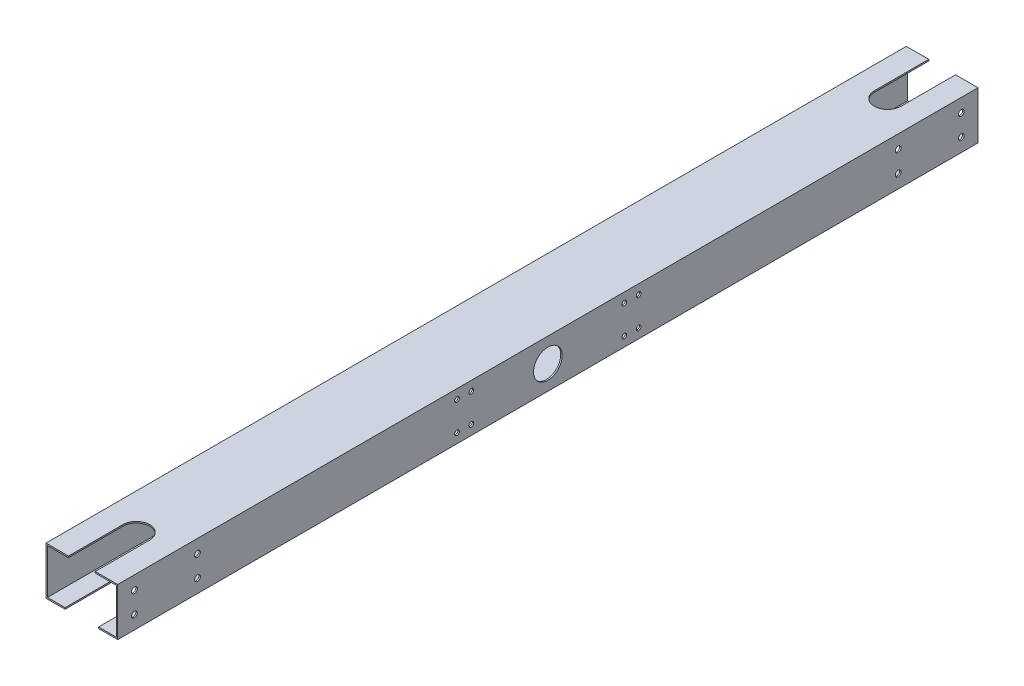
SolidWorks part; units mm, degrees
material "6061 Alloy"
ref_plane "Front Plane" through (0, 0, 0) normal (0, 0, 1) x (1, 0, 0)
ref_plane "Top Plane" through (0, 0, 0) normal (0, 1, 0) x (1, 0, 0)
ref_plane "Right Plane" through (0, 0, 0) normal (1, 0, 0) x (0, 0, -1)
sketch "Sketch1" plane through (0, 0, 0) normal (0, 0, 1) x (1, 0, 0)
  line L1 (-36, 23.5) -> (36, 23.5)
  line L2 (-36, 23.5) -> (-36, -23.5)
  line L3 (-36, -23.5) -> (36, -23.5)
  line L4 (36, 23.5) -> (36, -23.5)
  line L5 (-36, 23.5) -> (36, -23.5) construction
  line L6 (-36, -23.5) -> (36, 23.5) construction
  line L7 (-37.5, 25) -> (37.5, 25)
  line L8 (-37.5, 25) -> (-37.5, -25)
  line L9 (-37.5, -25) -> (37.5, -25)
  line L10 (37.5, 25) -> (37.5, -25)
  line L11 (-37.5, 25) -> (37.5, -25) construction
  line L12 (-37.5, -25) -> (37.5, 25) construction
  point P0 (0, 0)
  point P6 (0, 0)
  dimension "D1" = 75
  dimension "D2" = 72
  dimension "D3" = 50
  dimension "D4" = 47
extrude "Boss-Extrude1" add sketch "Sketch1" along normal blind 900
sketch "Sketch2" plane through (37.5, 0, 0) normal (1, 0, 0) x (0, 0, -1)
  line L1 (0, 0) -> (-900, 0) construction
  line L4 (-900, 25) -> (-900, -25) construction
  line L5 (-450, 25) -> (-450, -25) construction
  line L6 (-900, 25) -> (0, 25) construction
  line L7 (-900, -25) -> (0, -25) construction
  circle A3 centre (-450, 0) radius 15
  dimension "D1" = 30
extrude "Cut-Extrude1" cut sketch "Sketch2" against normal blind 59
sketch "Sketch3" plane through (0, 25, 0) normal (0, 1, 0) x (1, 0, 0)
  line L0 (0, -843) -> (0, -913.9861) construction
  line L5 (14, -843) -> (14, -913.9861)
  line L6 (-14, -843) -> (-14, -913.9861)
  line L7 (37.5, -900) -> (-37.5, -900) construction
  arc A0 (14, -843) -> (-14, -843) centre (0, -843) ccw
  arc A1 (-14, -913.9861) -> (14, -913.9861) centre (0, -913.9861) ccw
  point P2 (0, -878.4931)
  dimension "D2" = 14
  dimension "D1" = 57
extrude "Cut-Extrude2" cut sketch "Sketch3" against normal blind 10
sketch "Sketch4" plane through (0, -25, 0) normal (0, -1, 0) x (1, 0, 0)
  line L0 (0.0011, 850) -> (0.0011, 939.0785) construction
  line L1 (-17.4989, 850) -> (-17.4989, 939.0785)
  line L2 (17.5011, 850) -> (17.5011, 939.0785)
  line L3 (37.5, 900) -> (37.5, 0) construction
  line L4 (-37.5, 900) -> (37.5, 900) construction
  arc A0 (-17.4989, 850) -> (17.5011, 850) centre (0.0011, 850) ccw
  arc A1 (17.5011, 939.0785) -> (-17.4989, 939.0785) centre (0.0011, 939.0785) ccw
  point P2 (0.0011, 894.5393)
  dimension "D2" = 17.5
  dimension "D1" = 50
extrude "Cut-Extrude3" cut sketch "Sketch4" against normal blind 10
sketch "Sketch5" plane through (37.5, 0, 0) normal (1, 0, 0) x (0, 0, -1)
  line L0 (-900, -25) -> (0, -25) construction
  line L1 (-900, 25) -> (0, 25) construction
  line L2 (-900, -25) -> (-900, 25) construction
  line L3 (-849.5, 25) -> (-849.5, -25) construction
  circle A0 centre (-882.5, 11) radius 3
  circle A2 centre (-882.5, -11) radius 3
  circle A3 centre (-816.5, -11) radius 3
  circle A4 centre (-816.5, 11) radius 3
  dimension "D4" = 6
  dimension "D6" = 6
  dimension "D1" = 33
  dimension "D2" = 14
  dimension "D3" = 14
  dimension "D7" = 17.5
extrude "Cut-Extrude4" cut sketch "Sketch5" against normal blind 55
ref_plane "Plane1" through (0, 0, 450) normal (0, 0, 1) x (1, 0, 0)
mirror "Mirror1" about plane through (0, 0, 450) normal (0, 0, 1) of "Cut-Extrude4", "Cut-Extrude3", "Cut-Extrude2"
sketch "Sketch7" plane through (-37.5, 0, 0) normal (-1, 0, 0) x (0, 0, 1)
  line L0 (450, 40.085) -> (450, -40.085) construction
  line L1 (362.5, 25) -> (362.5, -25) construction
  line L2 (900, 25) -> (0, 25) construction
  line L3 (900, -25) -> (0, -25) construction
  line L4 (349.2272, 0) -> (389.8301, 0) construction
  line L5 (375.7728, 0) -> (335.1699, 0) construction
  line L6 (524.2272, 0) -> (564.8301, 0) construction
  line L7 (550.7728, 0) -> (510.1699, 0) construction
  line L8 (537.5, 25) -> (537.5, -25) construction
  line L9 (435, 0) -> (465, 0) construction
  circle A0 centre (355, 15) radius 2.5
  circle A1 centre (370, 15) radius 2.5
  circle A2 centre (370, -15) radius 2.5
  circle A3 centre (355, -15) radius 2.5
  circle A4 centre (545, -15) radius 2.5
  circle A5 centre (530, -15) radius 2.5
  circle A6 centre (530, 15) radius 2.5
  circle A7 centre (545, 15) radius 2.5
  circle A8 centre (450, 0) radius 15 construction
  point P21 (450, 25)
  point P36 (450, 0)
  dimension "D1" = 5
  dimension "D2" = 7.5
  dimension "D3" = 15
  dimension "D4" = 87.5
extrude "Cut-Extrude6" cut sketch "Sketch7" against normal through all
sketch "Sketch8" plane through (37.5, 0, 0) normal (1, 0, 0) x (0, 0, -1)
  circle A0 centre (-450, 0) radius 15
extrude "Cut-Extrude7" cut sketch "Sketch8" against normal blind 97
